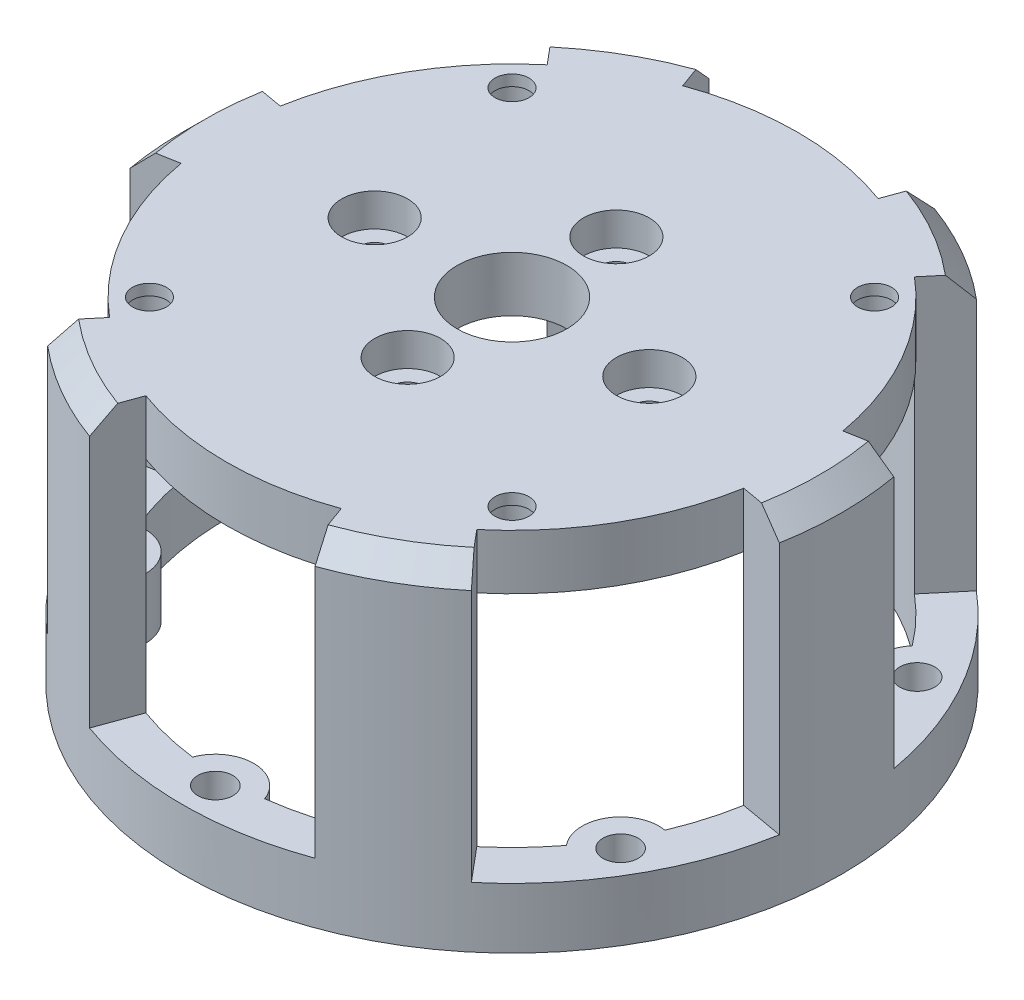
SolidWorks part; units mm, degrees
material "PLA"
ref_plane "Front Plane" through (0, 0, 0) normal (0, 0, 1) x (1, 0, 0)
ref_plane "Top Plane" through (0, 0, 0) normal (0, 1, 0) x (1, 0, 0)
ref_plane "Right Plane" through (0, 0, 0) normal (1, 0, 0) x (0, 0, -1)
sketch "Sketch1" plane through (0, 0, 0) normal (0, 1, 0) x (1, 0, 0)
  circle A0 centre (0, 0) radius 30
  dimension "D1" = 60
extrude "Boss-Extrude1" add sketch "Sketch1" along normal blind 30.5
sketch "Sketch4" plane through (0, 30.5, 0) normal (0, 1, 0) x (1, 0, 0)
  circle A0 centre (0, 0) radius 5
  dimension "D1" = 10
extrude "Cut-Extrude2" cut sketch "Sketch4" against normal up to surface (30.5 mm away) up to face at (0, 0, 30)
sketch "Sketch5" plane through (0, 30.5, 0) normal (0, 1, 0) x (1, 0, 0)
  line L0 (-12.8258, 35.2385) -> (-8.8925, 24.432)
  line L1 (0, 0) -> (0, 42.0141) construction
  line L2 (8.8925, 24.432) -> (12.8258, 35.2385)
  line L3 (-8.8925, 24.432) -> (0, 0) construction
  line L4 (0, 0) -> (8.8925, 24.432) construction
  arc A0 (8.8925, 24.432) -> (-8.8925, 24.432) centre (0, 0) ccw
  arc A1 (12.8258, 35.2385) -> (-12.8258, 35.2385) centre (0, 0) ccw
  dimension "D3" = 75
  dimension "D4" = 52
  dimension "D1" = 20
  dimension "D2" = 20
extrude "Cut-Extrude3" cut sketch "Sketch5" against normal blind 25
pattern_circular "CirPattern1" count 6 over 360 about axis through (0, 0, 0) along (0, 1, 0) of "Cut-Extrude3"
sketch "Sketch13" plane through (0, 0, 0) normal (0, -1, 0) x (1, 0, 0)
  circle A0 centre (0, 0) radius 26
  dimension "D1" = 52
extrude "Cut-Extrude4" cut sketch "Sketch13" against normal blind 25.5
chamfer "Chamfer1" distance 2 angle 45 6 edges at (15, 30.5, 25.9808) (30, 30.5, 0) (15, 30.5, -25.9808) (-15, 30.5, -25.9808) (-15, 30.5, 25.9808) (-30, 30.5, 0)
sketch "Sketch15" plane through (0, 0, 0) normal (0, -1, 0) x (1, 0, 0)
  line L0 (0, 0) -> (0, 27) construction
  line L1 (-3.3916, 27.8642) -> (3.3916, 27.8642)
  arc A0 (-3.3916, 27.8642) -> (3.3916, 27.8642) centre (0, 27) ccw
  dimension "D2" = 7
  dimension "D1" = 27
extrude "Boss-Extrude2" add sketch "Sketch15" against normal up to surface (5.5 mm away) up to face at (0, 5.5, 27.1557)
sketch "Sketch17" plane through (0, 0, 0) normal (0, -1, 0) x (1, 0, 0)
  circle A0 centre (0, 27) radius 1.6
  dimension "D1" = 3.2
extrude "Cut-Extrude5" cut sketch "Sketch17" against normal up to surface (5.5 mm away) up to face at (0, 5.5, 26.1098)
pattern_circular "CirPattern2" count 6 over 360 about axis through (0, 0, 0) along (0, 1, 0) of "Cut-Extrude5", "Boss-Extrude2"
sketch "Sketch19" plane through (0, 30.5, 0) normal (0, 1, 0) x (1, 0, 0)
  line L1 (16.5, 16.5) -> (-16.5, 16.5) construction
  line L2 (16.5, 16.5) -> (16.5, -16.5) construction
  line L3 (16.5, -16.5) -> (-16.5, -16.5) construction
  line L4 (-16.5, 16.5) -> (-16.5, -16.5) construction
  circle A0 centre (0, 0) radius 16.5 construction
  circle A1 centre (-16.5, 16.5) radius 1.55
  dimension "D1" = 33
  dimension "D2" = 3.1
extrude "Cut-Extrude6" cut sketch "Sketch19" against normal up to surface (5 mm away) up to face at (0, 25.5, 0)
sketch "Sketch20" plane through (0, 25.5, 0) normal (0, -1, 0) x (1, 0, 0)
  circle A0 centre (-16.5, -16.5) radius 2
  dimension "D1" = 4
extrude "Cut-Extrude7" cut sketch "Sketch20" against normal blind 4
pattern_circular "CirPattern3" count 4 over 360 about axis through (0, 0, 0) along (0, 1, 0) of "Cut-Extrude7", "Cut-Extrude6"
sketch "Sketch21" plane through (0, 30.5, 0) normal (0, 1, 0) x (1, 0, 0)
  circle A0 centre (0, 0) radius 9.5 construction
  circle A1 centre (0, 9.5) radius 1.5
  dimension "D1" = 19
  dimension "D2" = 3
extrude "Cut-Extrude8" cut sketch "Sketch21" against normal up to surface (5 mm away) up to face at (-18.5, 25.5, 16.5)
sketch "Sketch22" plane through (0, 30.5, 0) normal (0, 1, 0) x (1, 0, 0)
  circle A0 centre (0, 0) radius 12.5 construction
  circle A1 centre (-12.5, 0) radius 1.5
  dimension "D1" = 25
  dimension "D2" = 3
extrude "Cut-Extrude9" cut sketch "Sketch22" against normal up to surface (5 mm away) up to face at (0, 25.5, -11)
sketch "Sketch23" plane through (0, 30.5, 0) normal (0, 1, 0) x (1, 0, 0)
  circle A0 centre (0, 9.5) radius 3
  circle A1 centre (-12.5, 0) radius 3
  dimension "D1" = 6
extrude "Cut-Extrude10" cut sketch "Sketch23" against normal blind 3
pattern_circular "CirPattern5" count 2 over 360 about axis through (0, 0, 0) along (0, 1, 0) of "Cut-Extrude8", "Cut-Extrude10", "Cut-Extrude9"
